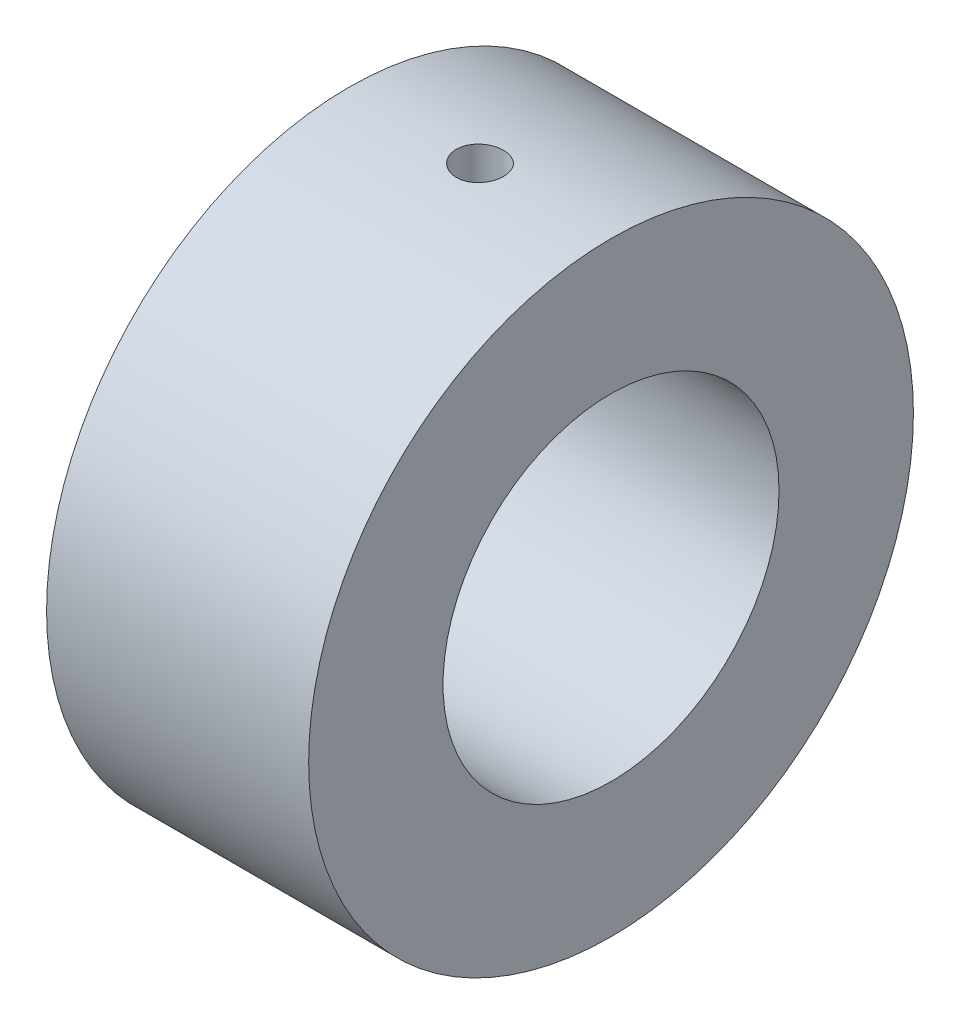
SolidWorks part; units mm, degrees
ref_plane "Front Plane" through (0, 0, 0) normal (0, 0, 1) x (1, 0, 0)
ref_plane "Top Plane" through (0, 0, 0) normal (0, 1, 0) x (1, 0, 0)
ref_plane "Right Plane" through (0, 0, 0) normal (1, 0, 0) x (0, 0, -1)
sketch "Sketch1" plane through (0, 0, 0) normal (0, 0, 1) x (1, 0, 0)
  line L0 (0, -39.0865) -> (0, 35.7212) construction
  line L1 (54.9038, 0) -> (-77.5962, 0) construction
  line L2 (19.5, 45) -> (-19.5, 45)
  line L3 (-19.5, 45) -> (-19.5, 25)
  line L4 (-19.5, 25) -> (19.5, 25)
  line L5 (19.5, 45) -> (19.5, 25)
  point P5 (0, 25)
  point P11 (0, 45)
  dimension "D1" = 20
  dimension "D2" = 39
  dimension "D3" = 90
revolve "Revolve1" add sketch "Sketch1" angle 360 about L1
sketch "Sketch2" plane through (0, 0, 0) normal (0, 1, 0) x (1, 0, 0)
  circle A0 centre (0, 0) radius 3.5107
extrude "Cut-Extrude1" cut sketch "Sketch2" along normal through all
